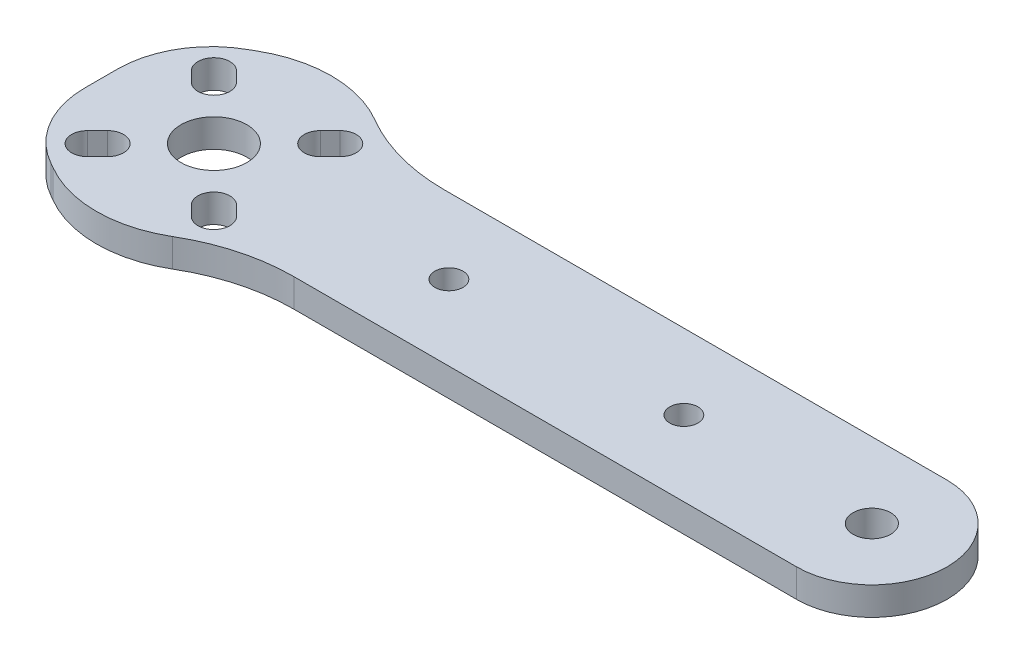
SolidWorks part; units mm, degrees
other "标注1"
sketch "草图10" plane through (158, 3, -12.5) normal (0.0162, 0.9997, -0.0168) x (0.5389, -0.0229, -0.8421)
other "标注2"
sketch "草图11" plane through (158, 3, -12.5) normal (0.0162, 0.9997, -0.0168) x (0.5389, -0.0229, -0.8421)
material "Thornel Mat VMA"
ref_plane "前视基准面" through (0, 0, 0) normal (0, 0, 1) x (1, 0, 0)
ref_plane "上视基准面" through (0, 0, 0) normal (0, 1, 0) x (1, 0, 0)
ref_plane "右视基准面" through (0, 0, 0) normal (1, 0, 0) x (0, 0, -1)
sketch "草图1" plane through (0, 0, 0) normal (0, 1, 0) x (1, 0, 0)
  line L0 (0, 0) -> (150, 0) construction
  line L1 (0, 8) -> (150, 8)
  line L2 (0, -8) -> (150, -8)
  arc A0 (0, 8) -> (0, -8) centre (0, 0) ccw
  arc A1 (150, -8) -> (150, 8) centre (150, 0) ccw
  point P3 (75, 0)
  dimension "D1" = 8
  dimension "D2" = 150
extrude "凸台-拉伸1" add sketch "草图1" along normal blind 3
sketch "草图8" plane through (0, 3, 0) normal (0, 1, 0) x (1, 0, 0)
  circle A0 centre (80, 0) radius 12.5
  dimension "D1" = 25
  dimension "D3" = 80
  dimension "D2" = 0
extrude "凸台-拉伸2" add sketch "草图8" against normal blind 3
sketch "草图2" plane through (0, 3, 0) normal (0, 1, 0) x (1, 0, 0)
  line L0 (80, 0) -> (85.6569, 5.6569) construction
  line L1 (150, 8) -> (89.6047, 8) construction
  line L2 (85.6569, 5.6569) -> (86.7175, 6.7175) construction
  line L5 (84.4562, 6.8575) -> (85.5169, 7.9181)
  line L6 (86.8575, 4.4562) -> (87.9181, 5.5169)
  line L7 (84.4562, -6.8575) -> (85.5169, -7.9181)
  line L8 (86.8575, -4.4562) -> (87.9181, -5.5169)
  line L9 (85.6569, -5.6569) -> (86.7175, -6.7175) construction
  line L10 (73.1425, -4.4562) -> (72.0819, -5.5169)
  line L11 (75.5438, -6.8575) -> (74.4831, -7.9181)
  line L12 (74.3431, -5.6569) -> (73.2825, -6.7175) construction
  line L13 (75.5438, 6.8575) -> (74.4831, 7.9181)
  line L14 (73.1425, 4.4562) -> (72.0819, 5.5169)
  line L15 (74.3431, 5.6569) -> (73.2825, 6.7175) construction
  circle A0 centre (80, 0) radius 3.5
  arc A7 (84.4562, 6.8575) -> (86.8575, 4.4562) centre (85.6569, 5.6569) ccw
  arc A8 (87.9181, 5.5169) -> (85.5169, 7.9181) centre (86.7175, 6.7175) ccw
  arc A9 (86.8575, -4.4562) -> (84.4562, -6.8575) centre (85.6569, -5.6569) ccw
  arc A10 (85.5169, -7.9181) -> (87.9181, -5.5169) centre (86.7175, -6.7175) ccw
  arc A11 (75.5438, -6.8575) -> (73.1425, -4.4562) centre (74.3431, -5.6569) ccw
  arc A12 (72.0819, -5.5169) -> (74.4831, -7.9181) centre (73.2825, -6.7175) ccw
  arc A13 (73.1425, 4.4562) -> (75.5438, 6.8575) centre (74.3431, 5.6569) ccw
  arc A14 (74.4831, 7.9181) -> (72.0819, 5.5169) centre (73.2825, 6.7175) ccw
  point P3 (86.1872, 6.1872)
  point P16 (80, 0)
  point P17 (86.1872, -6.1872)
  point P24 (73.8128, -6.1872)
  point P31 (73.8128, 6.1872)
  point P37 (80, 0)
  dimension "D2" = 8
  dimension "D3" = 45
  dimension "D4" = 9.5
  dimension "D6" = 7
  dimension "D1" = 80
  dimension "D7" = 0
  dimension "D8" = 0
  dimension "D5" = 4
extrude "切除-拉伸1" cut sketch "草图2" against normal through all
sketch "草图5" plane through (0, 3, 0) normal (0, 1, 0) x (1, 0, 0)
  circle A0 centre (10, 0) radius 1.5
  circle A1 centre (0, 5) radius 1.5
  circle A2 centre (0, -5) radius 1.5
  dimension "D1" = 3
  dimension "D2" = 3
  dimension "D3" = 3
  dimension "D4" = 5
  dimension "D5" = 5
  dimension "D6" = 10
extrude "切除-拉伸2" cut sketch "草图5" against normal through all
fillet "圆角3" radius 20 4 edges at (70.3953, 1.5, 8) (89.6047, 1.5, 8) (89.6047, 1.5, -8) (70.3953, 1.5, -8)
sketch "草图9" plane through (0, 3, 0) normal (0, 1, 0) x (1, 0, 0)
  circle A0 centre (150, 0) radius 2
  dimension "D1" = 4
extrude "切除-拉伸3" cut sketch "草图9" against normal through all
sketch "草图12" plane through (0, 3, 0) normal (0, 1, 0) x (1, 0, 0)
  line L1 (-18.5882, -13.1043) -> (68, -13.1043)
  line L2 (-18.5882, -13.1043) -> (-18.5882, 13.1043)
  line L3 (-18.5882, 13.1043) -> (68, 13.1043)
  line L4 (68, -13.1043) -> (68, 13.1043)
  line L5 (24.7059, 13.1043) -> (24.7059, -13.1043) construction
  line L6 (-18.5882, 0) -> (68, 0) construction
  circle A0 centre (80, 0) radius 3.5 construction
  point P0 (24.7059, 0)
  dimension "D1" = 12
extrude "切除-拉伸4" cut sketch "草图12" against normal through all
fillet "圆角4" radius 10 2 edges at (68, 1.5, 8.5128) (68, 1.5, -8.5128)
sketch "草图13" plane through (0, 3, 0) normal (0, 1, 0) x (1, 0, 0)
  circle A0 centre (105, 0) radius 1.5
  circle A1 centre (130, 0) radius 1.5
  circle A3 centre (80, 0) radius 3.5 construction
  dimension "D1" = 3
  dimension "D2" = 3
  dimension "D4" = 25
  dimension "D5" = 25
extrude "切除-拉伸5" cut sketch "草图13" against normal through all
